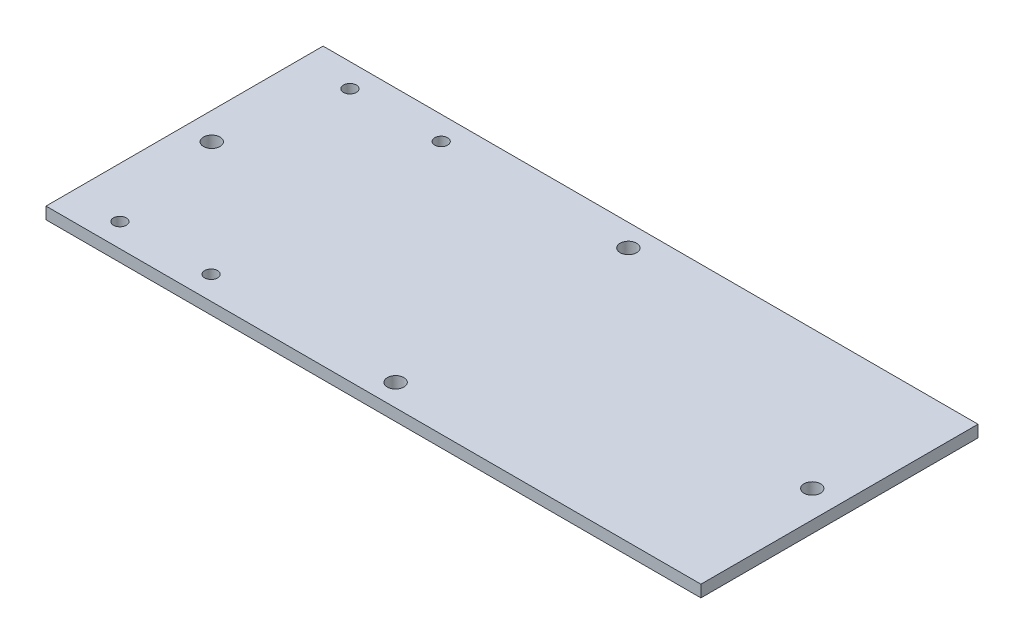
SolidWorks part; units mm, degrees
material "Thornel VCB-20 Carbon Cloth"
ref_plane "Front Plane" through (0, 0, 0) normal (0, 0, 1) x (1, 0, 0)
ref_plane "Top Plane" through (0, 0, 0) normal (0, 1, 0) x (1, 0, 0)
ref_plane "Right Plane" through (0, 0, 0) normal (1, 0, 0) x (0, 0, -1)
sketch "Sketch1" plane through (0, 0, 0) normal (0, 1, 0) x (1, 0, 0)
  line L1 (-82.55, -34.925) -> (82.55, -34.925)
  line L2 (-82.55, -34.925) -> (-82.55, 34.925)
  line L3 (-82.55, 34.925) -> (82.55, 34.925)
  line L4 (82.55, -34.925) -> (82.55, 34.925)
  dimension "D1" = 69.85
  dimension "D2" = 165.1
  dimension "D3" = 34.925
  dimension "D4" = 82.55
extrude "Boss-Extrude1" add sketch "Sketch1" along normal blind 3
sketch "Sketch2" plane through (0, 3, 0) normal (0, 1, 0) x (1, 0, 0)
  line L0 (-82.55, 34.925) -> (-82.55, -34.925) construction
  line L1 (82.55, -34.925) -> (82.55, 34.925) construction
  line L2 (82.55, 34.925) -> (-82.55, 34.925) construction
  line L3 (-82.55, -34.925) -> (82.55, -34.925) construction
  circle A0 centre (-77.47, 29.845) radius 1.5
  circle A1 centre (-77.47, -29.845) radius 1.5
  circle A2 centre (77.47, 29.845) radius 1.5
  circle A3 centre (77.47, -29.845) radius 1.5
  dimension "D1" = 3
  dimension "D2" = 3
  dimension "D3" = 3
  dimension "D4" = 3
  dimension "D5" = 5.08
  dimension "D6" = 5.08
  dimension "D7" = 5.08
  dimension "D8" = 5.08
  dimension "D9" = 5.08
  dimension "D10" = 5.08
  dimension "D11" = 5.08
  dimension "D12" = 5.08
sketch "Sketch3" plane through (0, 3, 0) normal (0, 1, 0) x (1, 0, 0)
  line L0 (-82.55, 34.925) -> (-82.55, -34.925) construction
  line L1 (82.55, -34.925) -> (82.55, 34.925) construction
  line L2 (-82.55, -34.925) -> (82.55, -34.925) construction
  line L3 (82.55, 34.925) -> (-82.55, 34.925) construction
  circle A0 centre (-75.692, 0) radius 2.0828
  circle A1 centre (75.692, 0) radius 2.0828
  circle A2 centre (0, -29.337) radius 2.0828
  circle A3 centre (0, 29.337) radius 2.0828
  point P16 (0, 0)
  point P17 (0, 0)
  point P18 (0, 0)
  dimension "D1" = 6.858
  dimension "D2" = 6.858
  dimension "D3" = 5.588
  dimension "D4" = 5.588
extrude "Cut-Extrude2" cut sketch "Sketch3" against normal blind 5.08
sketch "Sketch4" plane through (0, 3, 0) normal (0, 1, 0) x (1, 0, 0)
  line L0 (-82.55, 34.925) -> (-82.55, -34.925) construction
  line L1 (-46.85, -29) -> (-69.85, -29) construction
  line L2 (-46.85, -29) -> (-46.85, 29) construction
  line L3 (-46.85, 29) -> (-69.85, 29) construction
  line L4 (-69.85, -29) -> (-69.85, 29) construction
  line L5 (-46.85, -29) -> (-69.85, 29) construction
  line L6 (-46.85, 29) -> (-69.85, -29) construction
  circle A0 centre (-69.85, 29) radius 1.625
  circle A1 centre (-46.85, 29) radius 1.625
  circle A2 centre (-46.85, -29) radius 1.625
  circle A3 centre (-69.85, -29) radius 1.625
  point P0 (-58.35, 0)
  point P8 (-35.4796, 29)
  point P10 (0, 0)
  point P11 (-37.5555, -30.15)
  point P13 (-58.4114, -29)
  dimension "D3" = 3.25
  dimension "D1" = 58
  dimension "D2" = 23
  dimension "D4" = 12.7
extrude "Cut-Extrude3" cut sketch "Sketch4" against normal blind 17.78
